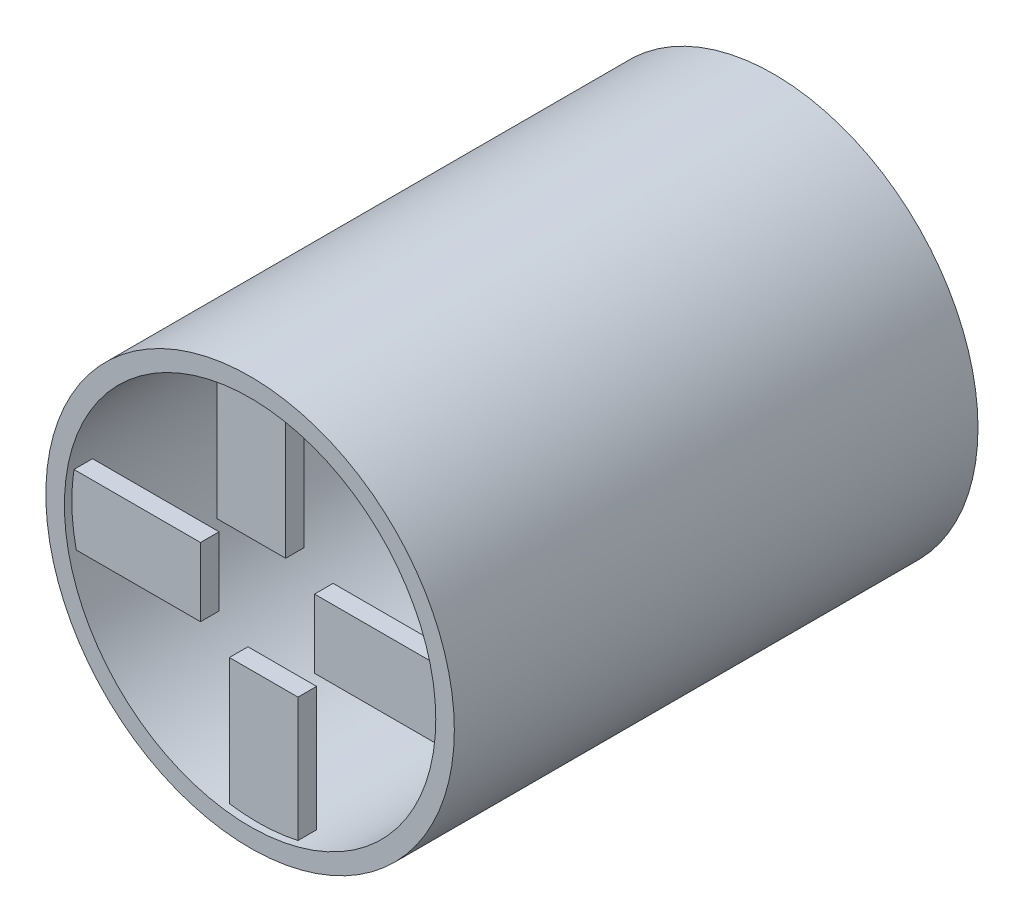
SolidWorks part; units mm, degrees
ref_plane "Plan de face" through (0, 0, 0) normal (0, 0, 1) x (1, 0, 0)
ref_plane "Plan de dessus" through (0, 0, 0) normal (0, 1, 0) x (1, 0, 0)
ref_plane "Plan de droite" through (0, 0, 0) normal (1, 0, 0) x (0, 0, -1)
sketch "Esquisse1" plane through (0, 0, 0) normal (0, 0, 1) x (1, 0, 0)
  circle A0 centre (0, 0) radius 2.5
  circle A1 centre (0, 0) radius 2.7497
  point P4 (0, 0)
extrude "Boss.-Extru.1" add sketch "Esquisse1" along normal blind 6.7
sketch "Esquisse2" plane through (0, 0, 6.7) normal (0, 0, 1) x (1, 0, 0)
  line L0 (2.4399, 0.5449) -> (0.7677, 0.5449)
  line L2 (-0.5449, 2.4399) -> (-0.5449, 0.7677)
  line L3 (-0.5449, 0.7677) -> (0.3787, 0.7677)
  line L4 (0.3787, 2.4712) -> (0.3787, 0.7677)
  line L5 (2.4712, -0.3787) -> (0.7677, -0.3787)
  line L6 (0.7677, 0.5449) -> (0.7677, -0.3787)
  line L7 (0.5449, -2.4399) -> (0.5449, -0.7677)
  line L8 (-0.3787, -2.4712) -> (-0.3787, -0.7677)
  line L9 (0.5449, -0.7677) -> (-0.3787, -0.7677)
  line L10 (-2.4399, -0.5449) -> (-0.7677, -0.5449)
  line L11 (-2.4712, 0.3787) -> (-0.7677, 0.3787)
  line L12 (-0.7677, -0.5449) -> (-0.7677, 0.3787)
  circle A0 centre (0, 0) radius 2.5 construction
  circle A1 centre (0, 0) radius 2.7497 construction
  arc A2 (-2.4399, -0.5449) -> (-0.3787, -2.4712) centre (0, 0) ccw
  circle A3 centre (0, 0) radius 2.7497
  arc A4 (-0.5449, 2.4399) -> (-2.4712, 0.3787) centre (0, 0) ccw
  arc A5 (2.4399, 0.5449) -> (0.3787, 2.4712) centre (0, 0) ccw
  arc A6 (0.5449, -2.4399) -> (2.4712, -0.3787) centre (0, 0) ccw
  point P25 (0, 0)
  dimension "D1" = 4
extrude "Boss.-Extru.2" add sketch "Esquisse2" along normal blind 0.25
sketch "Esquisse3" plane through (0, 0, 6.95) normal (0, 0, 1) x (1, 0, 0)
  circle A0 centre (0, 0) radius 2.5
  circle A1 centre (0, 0) radius 2.7497
  circle A2 centre (0, 0) radius 2.7497
  point P1 (0, 0)
  dimension "D1" = 0
extrude "Boss.-Extru.4" add sketch "Esquisse3" along normal blind 0.1
